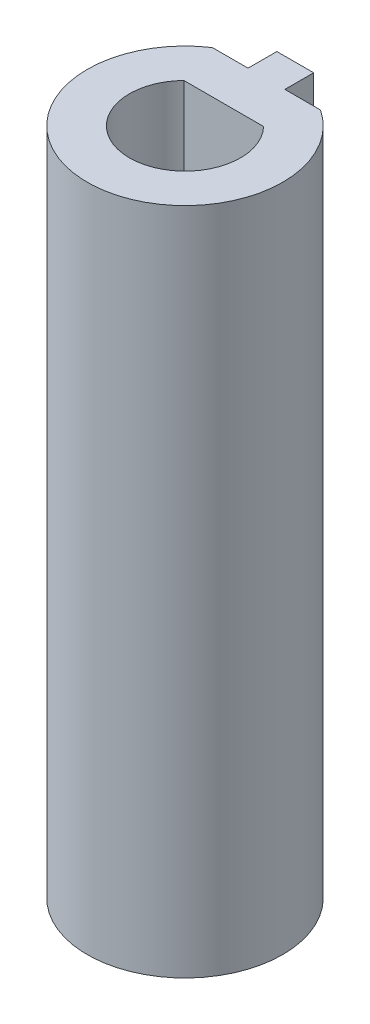
SolidWorks part; units mm, degrees
ref_plane "前视基准面" through (0, 0, 0) normal (0, 0, 1) x (1, 0, 0)
ref_plane "上视基准面" through (0, 0, 0) normal (0, 1, 0) x (1, 0, 0)
ref_plane "右视基准面" through (0, 0, 0) normal (1, 0, 0) x (0, 0, -1)
sketch "草图1" plane through (0, 0, 0) normal (0, 1, 0) x (1, 0, 0)
  line L0 (-1.1624, 1.1284) -> (1.1624, 1.1284)
  line L1 (0.5364, 2.375) -> (-1.5754, 2.375)
  line L2 (0, 2.2151) -> (0, 4.0985) construction
  line L3 (0, 2.2151) -> (0, 3.2151)
  line L4 (-0.5364, 3.2151) -> (0.5364, 3.2151)
  line L5 (0.5364, 3.2151) -> (0.5364, 2.375)
  line L6 (-0.5364, 3.2151) -> (-0.5364, 2.375)
  line L7 (-0.5364, 2.375) -> (1.5754, 2.375)
  arc A0 (-1.1624, 1.1284) -> (1.1624, 1.1284) centre (0, 0) ccw
  arc A2 (-1.5754, 2.375) -> (1.5754, 2.375) centre (0, 0) ccw
  point P1 (0, 0)
  point P7 (0, 1.1284)
  point P10 (0, 3.0338)
  point P15 (0, 3.2151)
  dimension "D1" = 1
  dimension "D2" = 1.62
  dimension "D3" = 2.85
extrude "凸台-拉伸1" add sketch "草图1" along normal blind 19.5
